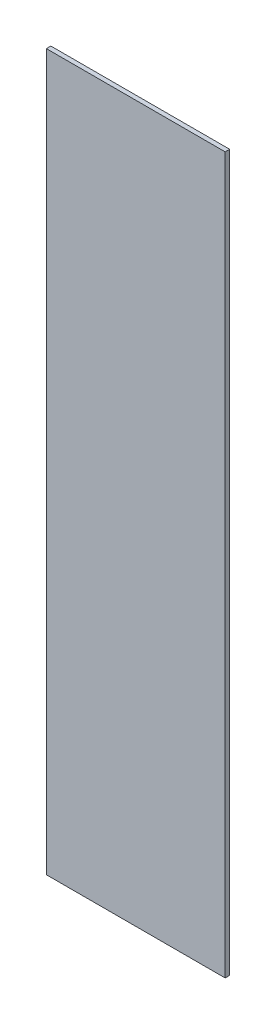
SolidWorks part; units mm, degrees
ref_plane "Alzado" through (0, 0, 0) normal (0, 0, 1) x (1, 0, 0)
ref_plane "Planta" through (0, 0, 0) normal (0, 1, 0) x (1, 0, 0)
ref_plane "Vista lateral" through (0, 0, 0) normal (1, 0, 0) x (0, 0, -1)
sketch "Croquis1" plane through (0, 0, 0) normal (0, 0, 1) x (1, 0, 0)
  line L1 (0, 0) -> (127, 0)
  line L2 (0, 0) -> (0, 508)
  line L3 (0, 508) -> (127, 508)
  line L4 (127, 0) -> (127, 508)
  dimension "D1" = 127
  dimension "D2" = 508
extrude "Saliente-Extruir1" add sketch "Croquis1" along normal blind 3.175
